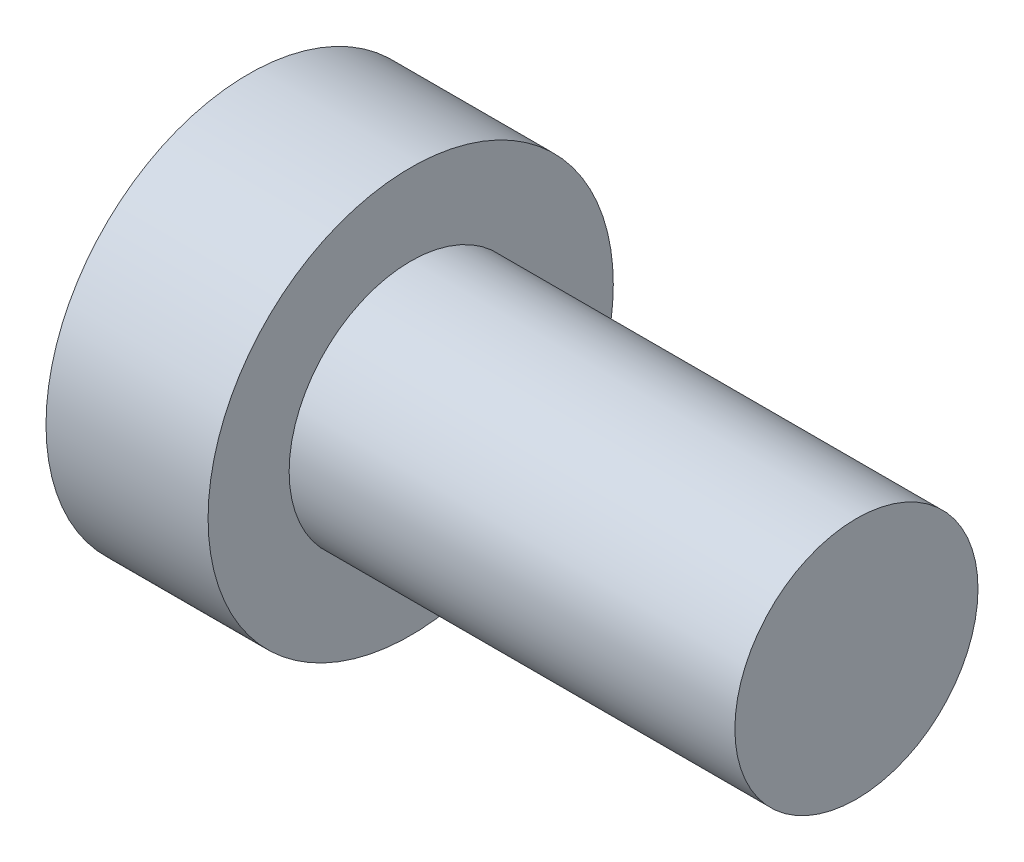
SolidWorks part; units mm, degrees
ref_plane "Alzado" through (0, 0, 0) normal (0, 0, 1) x (1, 0, 0)
ref_plane "Planta" through (0, 0, 0) normal (0, 1, 0) x (1, 0, 0)
ref_plane "Vista lateral" through (0, 0, 0) normal (1, 0, 0) x (0, 0, -1)
sketch "Sketch1" plane through (0, 0, 0) normal (0, 0, 1) x (1, 0, 0)
  line L0 (0, 0) -> (7.5, 0) construction
  line L1 (7.5, 0) -> (7.5, 1.5)
  line L2 (7.5, 1.5) -> (2, 1.5)
  line L3 (2, 1.5) -> (2, 2.5)
  line L4 (2, 2.5) -> (0, 2.5)
  line L5 (0, 2.5) -> (0, 0)
  line L6 (0, 0) -> (7.5, 0)
  point P3 (0, 0)
  dimension "D1" = 5.5
  dimension "D2" = 2
  dimension "D3" = 3
  dimension "D4" = 5
revolve "Revolve1" add sketch "Sketch1" angle 360 about L0
